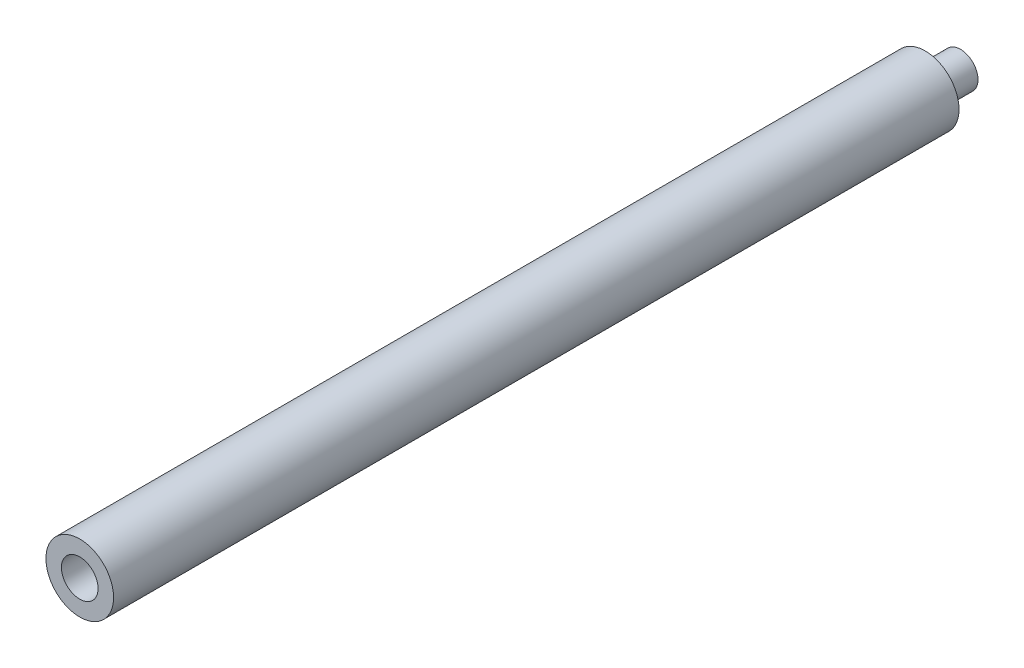
SolidWorks part; units mm, degrees
ref_plane "Front Plane" through (0, 0, 0) normal (0, 0, 1) x (1, 0, 0)
ref_plane "Top Plane" through (0, 0, 0) normal (0, 1, 0) x (1, 0, 0)
ref_plane "Right Plane" through (0, 0, 0) normal (1, 0, 0) x (0, 0, -1)
sketch "Sketch1" plane through (0, 0, 0) normal (0, 0, 1) x (1, 0, 0)
  line L0 (0, -2.4) -> (0, 2.4) construction
  circle A0 centre (0, 0) radius 2.4
  point P6 (0, 0)
  dimension "D2" = 4.8
extrude "Boss-Extrude1" add sketch "Sketch1" along normal blind 60
sketch "Sketch6" plane through (0, 0, 0) normal (0, 0, -1) x (-1, 0, 0)
  circle A0 centre (0, 0) radius 1.25
  dimension "D1" = 2.5
extrude "Boss-Extrude2" add sketch "Sketch6" along normal blind 2.5
sketch "Sketch7" plane through (0, 0, 60) normal (0, 0, 1) x (1, 0, 0)
  circle A0 centre (0, 0) radius 1.3
  dimension "D1" = 2.6
extrude "Cut-Extrude1" cut sketch "Sketch7" against normal blind 2.5
sketch "Sketch9" plane through (0, 0, 60) normal (0, 0, 1) x (1, 0, 0)
  circle A0 centre (0, 0) radius 2.4
  dimension "D1" = 4.8
